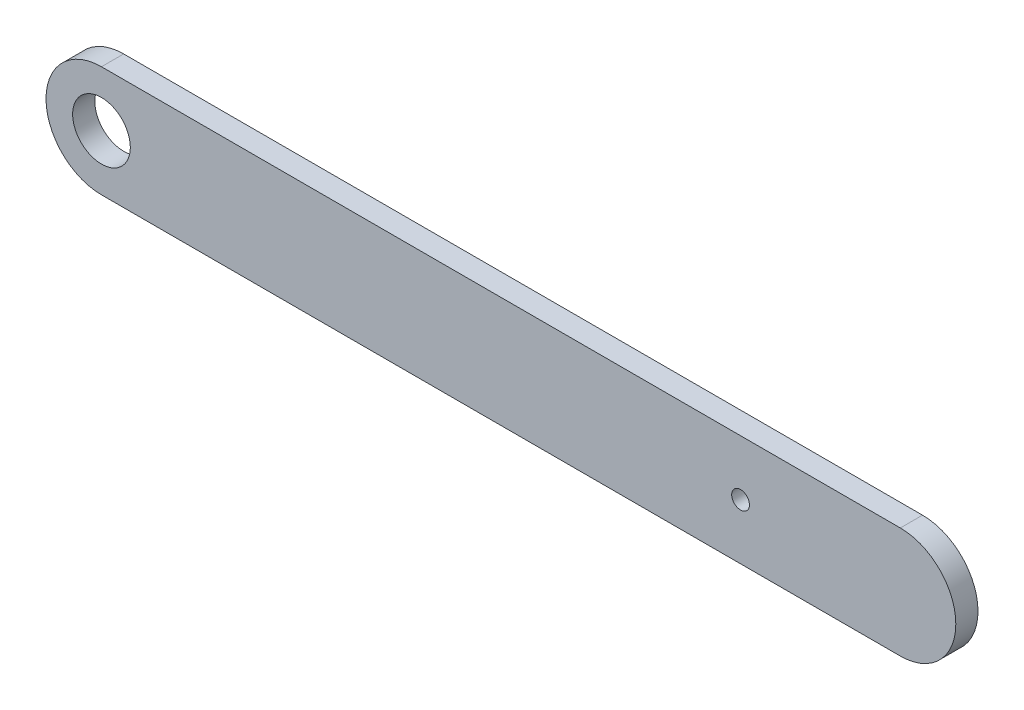
SolidWorks part; units mm, degrees
ref_plane "Front Plane" through (0, 0, 0) normal (0, 0, 1) x (1, 0, 0)
ref_plane "Top Plane" through (0, 0, 0) normal (0, 1, 0) x (1, 0, 0)
ref_plane "Right Plane" through (0, 0, 0) normal (1, 0, 0) x (0, 0, -1)
sketch "Sketch1" plane through (0, 0, 0) normal (0, 0, 1) x (1, 0, 0)
  line L0 (0, 0) -> (180, 0) construction
  line L1 (0, 12.5) -> (180, 12.5)
  line L2 (0, -12.5) -> (180, -12.5)
  arc A0 (0, 12.5) -> (0, -12.5) centre (0, 0) ccw
  arc A1 (180, -12.5) -> (180, 12.5) centre (180, 0) ccw
  circle A2 centre (0, 0) radius 6.5
  circle A3 centre (144, 0) radius 2
  point P3 (90, 0)
  dimension "D3" = 13
  dimension "D5" = 4
  dimension "D1" = 180
  dimension "D2" = 25
  dimension "D4" = 144
extrude "Boss-Extrude1" add sketch "Sketch1" along normal blind 5
sketch "Sketch2" plane through (0, -12.5, 0) normal (0, -1, 0) x (1, 0, 0)
  line L0 (180, 5) -> (180, 0) construction
  circle A0 centre (175, 2.5) radius 1.6
  point P4 (180, 2.5)
  dimension "D1" = 3.2
  dimension "D2" = 5
extrude "Cut-Extrude1" cut sketch "Sketch2" against normal blind 10
